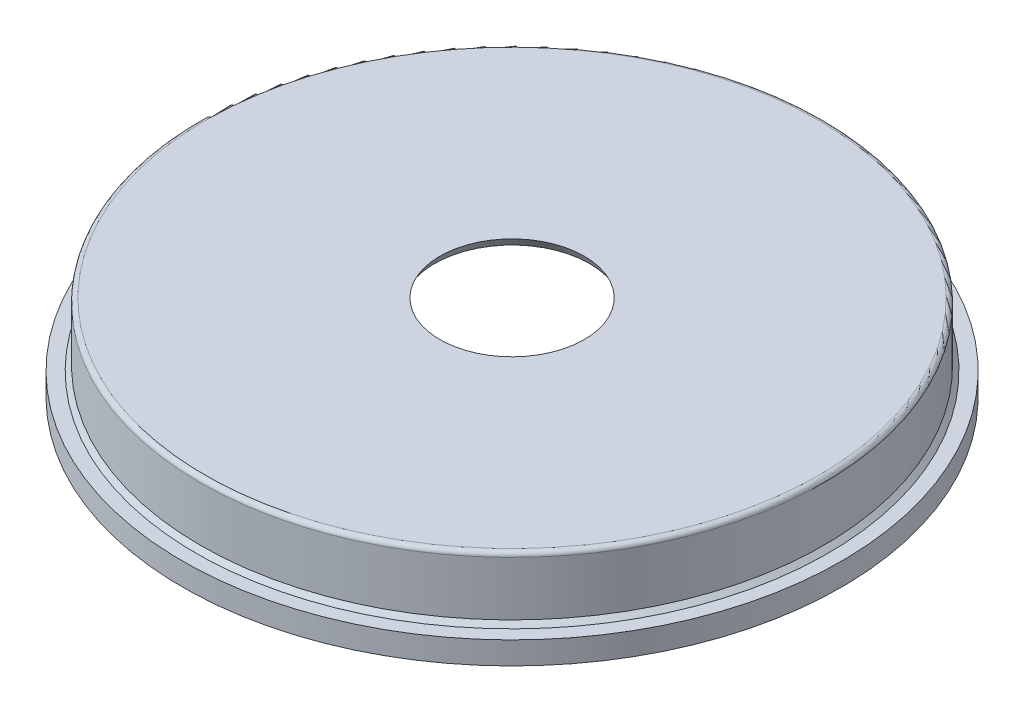
SolidWorks part; units mm, degrees
material "Cotton Phenolics Linen Reinforced"
ref_plane "Piano frontale" through (0, 0, 0) normal (0, 0, 1) x (1, 0, 0)
ref_plane "Piano superiore" through (0, 0, 0) normal (0, 1, 0) x (1, 0, 0)
ref_plane "Piano destro" through (0, 0, 0) normal (1, 0, 0) x (0, 0, -1)
sketch "Schizzo1" plane through (0, 0, 0) normal (1, 0, 0) x (0, 0, -1)
  line L0 (-73, 0) -> (-72, 0)
  line L1 (-72, 0) -> (-72, 3)
  line L2 (-72, 3) -> (-67, 3)
  line L4 (-70, 5) -> (-73, 5)
  line L5 (-73, 5) -> (-73, 0)
  line L6 (0, 0) -> (0, 22.5413) construction
  line L7 (-69, 6) -> (-69, 18)
  line L8 (-68, 19) -> (-16, 19)
  line L10 (-17.1547, 17) -> (-67, 17)
  line L11 (-67, 17) -> (-67, 3)
  line L12 (-70, 5) -> (-69, 6)
  line L13 (-16, 19) -> (-17.1547, 17)
  arc A0 (-69, 18) -> (-68, 19) centre (-68, 18) cw
  dimension "D12" = 1
  dimension "D1" = 146
  dimension "D2" = 1
  dimension "D3" = 2
  dimension "D4" = 3
  dimension "D5" = 4
  dimension "D6" = 6
  dimension "D7" = 14
  dimension "D8" = 2
  dimension "D9" = 53
  dimension "D10" = 45
  dimension "D11" = 3
  dimension "D13" = 60
revolve "Rivoluzione1" add sketch "Schizzo1" angle 360 about L6
